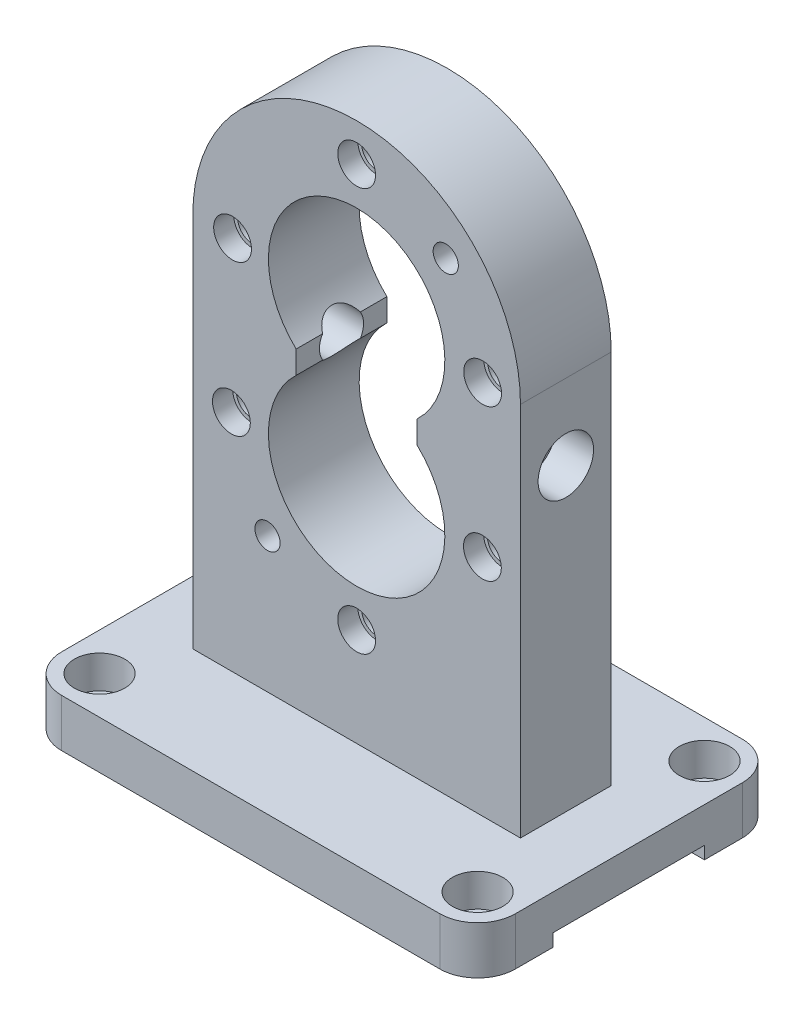
SolidWorks part; units mm, degrees
ref_plane "Front Plane" through (0, 0, 0) normal (0, 0, 1) x (1, 0, 0)
ref_plane "Top Plane" through (0, 0, 0) normal (0, 1, 0) x (1, 0, 0)
ref_plane "Right Plane" through (0, 0, 0) normal (1, 0, 0) x (0, 0, -1)
sketch "Sketch1" plane through (0, 0, 0) normal (0, 1, 0) x (1, 0, 0)
  line L1 (-75, -60) -> (75, -60)
  line L2 (-90, -45) -> (-90, 45)
  line L3 (-75, 60) -> (75, 60)
  line L4 (90, -45) -> (90, 45)
  line L5 (-90, -60) -> (90, 60) construction
  line L6 (-90, 60) -> (90, -60) construction
  arc A0 (75, -60) -> (90, -45) centre (75, -45) ccw
  arc A1 (75, 60) -> (90, 45) centre (75, 45) cw
  arc A2 (-75, -60) -> (-90, -45) centre (-75, -45) cw
  arc A3 (-90, 45) -> (-75, 60) centre (-75, 45) cw
  point P0 (0, 0)
  dimension "D3" = 15
  dimension "D1" = 120
  dimension "D2" = 180
extrude "Boss-Extrude1" add sketch "Sketch1" along normal blind 19
hole_wizard "CBORE for M6 Hex Head Bolt1" positions "3DSketch1" profile "Sketch2" counterbore size "M6" standard "ANSI Metric" end condition through all
sketch3d "3DSketch1"
  line L0 (-75, 19, 45) -> (-75, 0, 45) construction
  line L1 (-75, 19, -45) -> (-75, 0, -45) construction
  line L2 (75, 19, -45) -> (75, 0, -45) construction
  line L3 (75, 19, 45) -> (75, 0, 45) construction
  point P0 (-75, 19, 45)
  point P4 (-75, 19, -45)
  point P8 (75, 19, -45)
  point P12 (75, 19, 45)
sketch "Sketch2" plane through (-75, 19, 45) normal (1, 0, 0) x (0, 0, 1)
  line L0 (0, 0) -> (0, 19)
  line L1 (0, 19) -> (7.5, 19)
  line L3 (7.5, 19) -> (7.5, 13)
  line L4 (7.5, 13) -> (10, 13)
  line L5 (10, 13) -> (10, 0)
  line L7 (10, 0) -> (0, 0)
  line L11 (0, -6.35) -> (0, 107.95) construction
  dimension "Thru Hole Dia." = 15
  dimension "Thru Hole Depth" = 19
  dimension "C'Bore Dia." = 20
  dimension "C'Bore Depth" = 13
ref_plane "Plane1" through (0, 0, 18) normal (0, 0, 1) x (1, 0, 0)
sketch "Sketch3" plane through (0, 0, 18) normal (0, 0, 1) x (1, 0, 0)
  line L0 (0, 0) -> (0, 168) construction
  line L1 (-65, 168) -> (-65, 0)
  line L2 (-75, 0) -> (75, 0) construction
  line L3 (65, 168) -> (65, 0)
  line L4 (65, 0) -> (-65, 0)
  arc A0 (65, 168) -> (-65, 168) centre (0, 168) ccw
  dimension "D2" = 130
  dimension "D1" = 168
extrude "Boss-Extrude2" add sketch "Sketch3" against normal blind 36
sketch "Sketch4" plane through (0, 0, 18) normal (0, 0, 1) x (1, 0, 0)
  line L0 (90, 19) -> (90, 0) construction
  line L1 (24, 142.5245) -> (24, 133.4755)
  line L2 (65, 19) -> (65, 168) construction
  line L3 (0, 108) -> (0, 168) construction
  line L4 (-24, 142.5245) -> (-24, 133.4755)
  arc A0 (24, 142.5245) -> (-24, 142.5245) centre (0, 168) ccw
  arc A1 (-24, 133.4755) -> (24, 133.4755) centre (0, 108) ccw
  dimension "D1" = 70
  dimension "D2" = 70
  dimension "D3" = 60
  dimension "D4" = 168
  dimension "D5" = 90
  dimension "D6" = 41
extrude "Cut-Extrude1" cut sketch "Sketch4" against normal blind 36
hole_wizard "CBORE for M16 Hex Head Bolt1" positions "3DSketch2" profile "Sketch5" counterbore size "M16" standard "ANSI Metric"
sketch3d "3DSketch2"
  line L6 (65, 19, 0) -> (65, 132.7979, 0) construction
  line L7 (65, 19, 18) -> (65, 19, -18) construction
  point P0 (65, 138, 0)
  dimension "D1" = 119
sketch "Sketch5" plane through (65, 138, 0) normal (0, 1, 0) x (0, 0, -1)
  line L0 (0, 0) -> (0, 41)
  line L1 (0, 41) -> (8.75, 41)
  line L3 (8.75, 41) -> (8.75, 15)
  line L4 (8.75, 15) -> (11, 15)
  line L5 (11, 15) -> (11, 0)
  line L7 (11, 0) -> (0, 0)
  line L11 (0, -6.35) -> (0, 107.95) construction
  dimension "Thru Hole Dia." = 17.5
  dimension "Thru Hole Depth" = 41
  dimension "C'Bore Dia." = 22
  dimension "C'Bore Depth" = 15
ref_plane "Plane2" through (0, 0, 0) normal (1, 0, 0) x (0, 0, -1)
mirror "Mirror1" about plane through (0, 0, 0) normal (1, 0, 0) of "CBORE for M16 Hex Head Bolt1"
hole_wizard "CBORE for M5 Hex Head Bolt1" positions "3DSketch5" profile "Sketch7" counterbore size "M5" standard "ANSI Metric" end condition up to next
sketch3d "3DSketch5"
  line L6 (0, 108, -18) -> (0, 108, 18) construction
  line L10 (0, 168, -18) -> (0, 168, 18) construction
  line L14 (0, 168, -18) -> (0, 168, 18) construction
  line L15 (0, 168, 18) -> (65, 168, 18) construction
  line L16 (65, 168, 18) -> (-65, 168, 18) construction
  line L18 (0, 168, 18) -> (0, 233, 18) construction
  line L22 (0, 108, 18) -> (-65, 108, 18) construction
  line L23 (-65, 168, 18) -> (-65, 19, 18) construction
  line L24 (-65, 108, 18) -> (65, 108, 18) construction
  line L25 (65, 19, 18) -> (65, 168, 18) construction
  line L27 (0, 233, 18) -> (0, 19, 18) construction
  line L28 (-65, 19, 18) -> (65, 19, 18) construction
  circle A5 centre (0, 168, 18) radius 50 construction
  circle A6 centre (0, 108, 18) radius 50 construction
  arc A7 (65, 168, 18) -> (-65, 168, 18) centre (0, 168, 18) ccw construction
  point P0 (0, 218, 18)
  point P2 (-49.2253, 168, 18)
  point P4 (-49.6877, 108, 18)
  point P6 (0, 58, 18)
  point P8 (49.8978, 108, 18)
  point P10 (49.9912, 168, 18)
  point P66 (0, 168, 68)
  point P72 (0, 108, 68)
  point P86 (0, 168, 83)
  dimension "D7" = 100
  dimension "D1" = 100
sketch "Sketch7" plane through (0, 218, 18) normal (1, 0, 0) x (0, -1, 0)
  line L0 (0, 0) -> (0, 36)
  line L1 (0, 36) -> (6, 36)
  line L3 (6, 36) -> (6, 8)
  line L4 (6, 8) -> (7.5, 8)
  line L5 (7.5, 8) -> (7.5, 0)
  line L7 (7.5, 0) -> (0, 0)
  line L11 (0, -6.35) -> (0, 107.95) construction
  dimension "Thru Hole Dia." = 12
  dimension "Thru Hole Depth" = 36
  dimension "C'Bore Dia." = 15
  dimension "C'Bore Depth" = 8
sketch "Sketch9" plane through (90, 0, 0) normal (1, 0, 0) x (0, 0, -1)
  line L0 (-45, 0) -> (45, 0) construction
  line L1 (-30, 0) -> (30, 0)
  line L2 (-30, 0) -> (-30, 5)
  line L3 (-30, 5) -> (30, 5)
  line L4 (30, 0) -> (30, 5)
  dimension "D1" = 30
  dimension "D2" = 60
  dimension "D3" = 5
extrude "Cut-Extrude2" cut sketch "Sketch9" against normal through all
hole_wizard "Ø10.0mm Dowel Hole1" positions "3DSketch6" profile "Sketch11" hole size "Ø10.0" standard "ANSI Metric"
sketch3d "3DSketch6"
  line L0 (0, 168, -18) -> (0, 168, 18) construction
  line L1 (0, 108, -18) -> (0, 108, 18) construction
  line L4 (0, 168, 18) -> (65, 168, 18) construction
  line L6 (0, 168, 18) -> (35.3553, 203.3553, 18) construction
  line L7 (0, 108, 18) -> (-65, 108, 18) construction
  line L8 (-65, 168, 18) -> (-65, 19, 18) construction
  line L10 (0, 108, 18) -> (-35.3553, 72.6447, 18) construction
  circle A1 centre (0, 168, 18) radius 50 construction
  circle A2 centre (0, 108, 18) radius 50 construction
  point P0 (35.3553, 203.3553, 18)
  point P2 (-35.3553, 72.6447, 18)
  point P10 (3.9753, 164.0247, 67.6829)
  point P15 (-3.7173, 111.7173, 67.7229)
  point P38 (0, 108, 18)
  dimension "D1" = 100
  dimension "D2" = 100
  dimension "D4" = 45
  dimension "D3" = 45
sketch "Sketch11" plane through (35.3553, 203.3553, 18) normal (1, 0, 0) x (0, -1, 0)
  line L0 (0, 0) -> (0, 39.0043)
  line L1 (0, 39.0043) -> (5, 36)
  line L2 (5, 36) -> (5, 0)
  line L5 (5, 0) -> (0, 0)
  line L10 (0, 39.0043) -> (-5, 36) construction
  line L11 (0, -6.35) -> (0, 107.95) construction
  dimension "Hole Dia." = 10
  dimension "Hole Depth" = 36
  dimension "Drill Angle" = 118
sketch "Sketch12" plane through (0, 0, -18) normal (0, 0, -1) x (-1, 0, 0)
  circle A0 centre (0, 218) radius 7.5
  circle A1 centre (-49.9912, 168) radius 7.5
  circle A2 centre (-49.8978, 108) radius 7.5
  circle A3 centre (49.6877, 108) radius 7.5
  circle A4 centre (49.2253, 168) radius 7.5
  circle A5 centre (0, 58) radius 7.5
  dimension "D1" = 15
  dimension "D2" = 15
  dimension "D3" = 15
  dimension "D4" = 15
  dimension "D5" = 15
  dimension "D6" = 15
extrude "Cut-Extrude3" cut sketch "Sketch12" against normal blind 8
